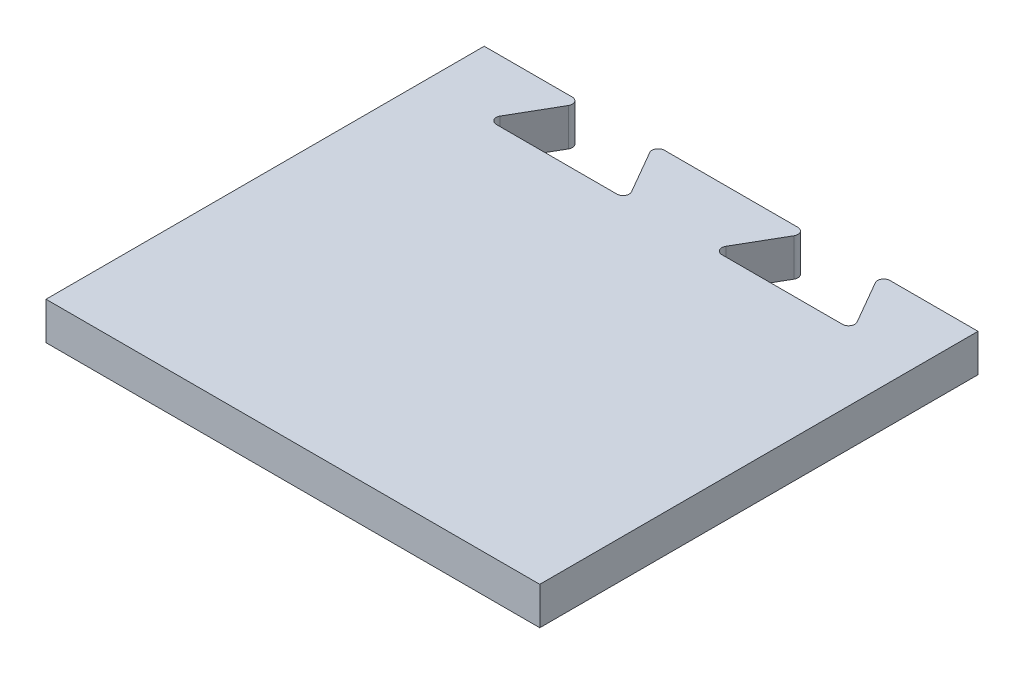
SolidWorks part; units mm, degrees
ref_plane "Front Plane" through (0, 0, 0) normal (0, 0, 1) x (1, 0, 0)
ref_plane "Top Plane" through (0, 0, 0) normal (0, 1, 0) x (1, 0, 0)
ref_plane "Right Plane" through (0, 0, 0) normal (1, 0, 0) x (0, 0, -1)
sketch "Sketch1" plane through (0, 0, 0) normal (0, 1, 0) x (1, 0, 0)
  line L0 (0, 0) -> (0, 35.5)
  line L1 (0, 35.5) -> (8, 35.5)
  line L2 (8, 35.5) -> (5.1132, 30.5)
  line L3 (5.1132, 30.5) -> (16.6132, 30.5)
  line L4 (16.6132, 30.5) -> (13.7265, 35.5)
  line L5 (13.7265, 35.5) -> (26.2735, 35.5)
  line L6 (26.2735, 35.5) -> (23.3868, 30.5)
  line L7 (23.3868, 30.5) -> (34.8868, 30.5)
  line L8 (34.8868, 30.5) -> (32, 35.5)
  line L9 (32, 35.5) -> (40, 35.5)
  line L10 (40, 35.5) -> (40, 0)
  line L11 (40, 0) -> (0, 0)
  dimension "D1" = 35.5
  dimension "D2" = 40
  dimension "D3" = 8
  dimension "D4" = 11.5
  dimension "D5" = 11.5
  dimension "D6" = 8
  dimension "D7" = 5
  dimension "D8" = 5
  dimension "D9" = 5
  dimension "D10" = 5
  dimension "D11" = 60
  dimension "D12" = 60
  dimension "D13" = 60
extrude "Boss-Extrude1" add sketch "Sketch1" along normal blind 3.05
fillet "Fillet3" radius 0.5 8 edges at (34.8868, 1.525, -30.5) (32, 1.525, -35.5) (23.3868, 1.525, -30.5) (26.2735, 1.525, -35.5) (13.7265, 1.525, -35.5) (16.6132, 1.525, -30.5) (5.1132, 1.525, -30.5) (8, 1.525, -35.5)
